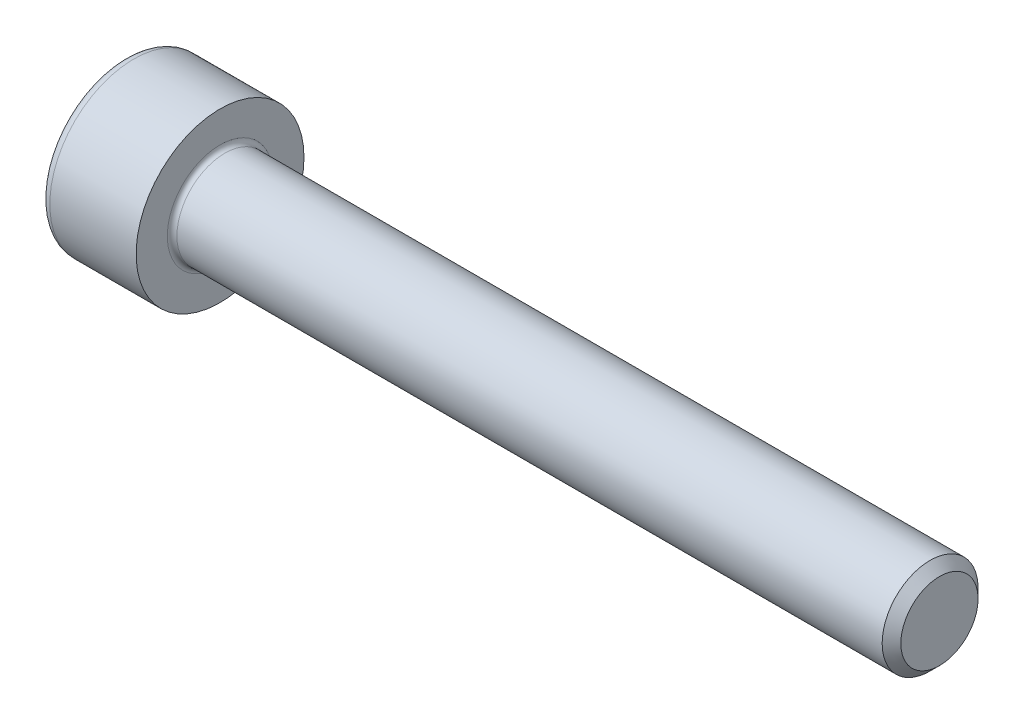
SolidWorks part; units mm, degrees
ref_plane "Front Plane" through (0, 0, 0) normal (0, 0, 1) x (1, 0, 0)
ref_plane "Top Plane" through (0, 0, 0) normal (0, 1, 0) x (1, 0, 0)
ref_plane "Right Plane" through (0, 0, 0) normal (1, 0, 0) x (0, 0, -1)
sketch "BaseHeadSke" plane through (0, 0, 0) normal (1, 0, 0) x (0, 0, -1)
  circle A1 centre (0, 0) radius 3.5
  dimension "Head_diameter" = 7
extrude "BaseHead" add sketch "BaseHeadSke" along normal blind 4
sketch "BodySke" plane through (0, 0, 0) normal (0, 0, 1) x (1, 0, 0)
  line L0 (0, 0) -> (34, 0)
  line L1 (34, 0) -> (34, 1.61)
  line L2 (34, 1.61) -> (33.61, 2)
  line L3 (33.61, 2) -> (0, 2)
  line L4 (0, 2) -> (0, 0)
  line L6 (0, 0) -> (159.3976, 0) construction
  line L7 (14, -84.3176) -> (14, 77.7215) construction
  line L8 (33.3, -21.5941) -> (33.3, 39.2994) construction
  line L10 (4, -3.5) -> (4, 3.5) construction
  dimension "Ang" = 45
  dimension "Diameter" = 4
  dimension "Minor_dia" = 3.22
  dimension "Thread_length" = 20
  dimension "Advance" = 0.7
  dimension "Length" = 30
revolve "BaseBody" add sketch "BodySke" angle 360 about L6
cosmetic thread "ThreadCosmetic" [suppressed] parameters "Thread_length"=20, "Thread_minor"=3.22
sketch "CutSocketSke" plane through (0, 0, 0) normal (1, 0, 0) x (0, 0, -1)
  line L1 (0, 1.7321) -> (-1.5, 0.866)
  line L2 (-1.5, 0.866) -> (-1.5, -0.866)
  line L3 (-1.5, -0.866) -> (0, -1.7321)
  line L4 (0, -1.7321) -> (1.5, -0.866)
  line L5 (1.5, -0.866) -> (1.5, 0.866)
  line L6 (1.5, 0.866) -> (0, 1.7321)
  circle A0 centre (0, 0) radius 1.5 construction
  dimension "Socket_width" = 3
extrude "CutSocket" cut sketch "CutSocketSke" along normal blind 2
sketch "CutHoleSke" plane through (0, 0, 0) normal (0, 0, 1) x (1, 0, 0)
  line L0 (0, 0) -> (149.4323, 0) construction
  line L1 (0, 1.5) -> (2.6, 1.5)
  line L2 (2.6, 1.5) -> (3.466, 0)
  line L3 (3.466, 0) -> (0, 0)
  line L4 (0, 0) -> (0, 1.5)
  line L6 (4, -3.5) -> (4, 3.5) construction
  dimension "D1" = 60
  dimension "Hole_depth" = 1.4
  dimension "D2" = 3
revolve "CutHole" cut sketch "CutHoleSke" angle 360 about L0
fillet "Fillet1" radius 0.2 1 edges at (4, 0, -2)
fillet "Fillet2" radius 0.4 1 edges at (0, 0, -3.5)
sketch "ThdSchSke" plane through (0, 0, 0) normal (0, 0, 1) x (1, 0, 0)
  line L0 (33.0748, 2.4503) -> (33.0748, 2)
  line L1 (33.0748, 2) -> (33.3, 1.61)
  line L2 (33.3, 1.61) -> (33.5252, 2)
  line L3 (33.5252, 2) -> (33.5252, 2.4503)
  line L4 (33.5252, 2.4503) -> (33.0748, 2.4503)
  line L6 (0, 0) -> (141.9934, 0) construction
  line L7 (34, -1.61) -> (34, 1.61) construction
  dimension "Advance" = 0.7
  dimension "D2" = 3.22
  dimension "D3" = 4
revolve "ThreadSchematic" [suppressed] cut sketch "ThdSchSke" angle 360 about L6
pattern_linear "ThdSchPat" [suppressed] count 27 spacing 0.7 along (1, 0, 0)
equation "\"Thread_minor@ThreadCosmetic\" = \"Minor_dia@BodySke\""
equation "\"Thread_length@ThreadCosmetic\" = \"Thread_length@BodySke\""
equation "\"D2@CutHoleSke\" = \"Socket_width@CutSocketSke\""
equation "\"D2@ThdSchSke\" = \"Minor_dia@BodySke\""
equation "\"D3@ThdSchSke\" = \"Diameter@BodySke\""
equation "\"Advance@ThdSchSke\" = \"Advance@BodySke\""
equation "\"D3@ThdSchPat\" = \"Advance@BodySke\""
equation "\"D1@ThdSchPat\" =  int( \"Thread_length@BodySke\"/\"Advance@BodySke\" )-1"
